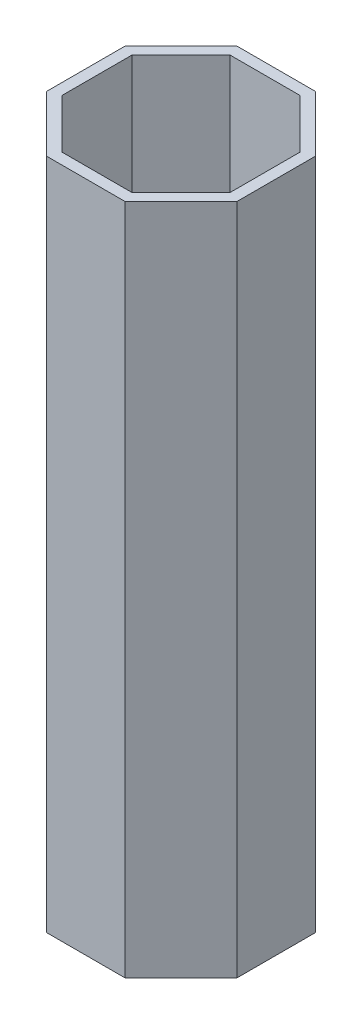
SolidWorks part; units mm, degrees
ref_plane "Alzado" through (0, 0, 0) normal (0, 0, 1) x (1, 0, 0)
ref_plane "Planta" through (0, 0, 0) normal (0, 1, 0) x (1, 0, 0)
ref_plane "Vista lateral" through (0, 0, 0) normal (1, 0, 0) x (0, 0, -1)
sketch "Croquis1" plane through (0, 0, 0) normal (0, 1, 0) x (1, 0, 0)
  line L0 (0, 0) -> (0, 30.3027) construction
  line L1 (17, -7.0416) -> (17, 7.0416)
  line L2 (17, 7.0416) -> (7.0416, 17)
  line L3 (7.0416, 17) -> (-7.0416, 17)
  line L4 (-7.0416, 17) -> (-17, 7.0416)
  line L5 (-17, 7.0416) -> (-17, -7.0416)
  line L6 (-17, -7.0416) -> (-7.0416, -17)
  line L7 (-7.0416, -17) -> (7.0416, -17)
  line L8 (7.0416, -17) -> (17, -7.0416)
  circle A0 centre (0, 0) radius 17 construction
  circle A1 centre (0, 11) radius 1.55
  circle A2 centre (0, 0) radius 4
  circle A3 centre (7.7782, 7.7782) radius 1.55
  circle A4 centre (11, 0) radius 1.55
  circle A5 centre (7.7782, -7.7782) radius 1.55
  circle A6 centre (0, -11) radius 1.55
  circle A7 centre (-7.7782, -7.7782) radius 1.55
  circle A8 centre (-11, 0) radius 1.55
  circle A9 centre (-7.7782, 7.7782) radius 1.55
  point P32 (0, 0)
  dimension "D1" = 34
  dimension "D2" = 3.1
  dimension "D3" = 11
  dimension "D4" = 8
  dimension "D5" = 8
extrude "Saliente-Extruir1" add sketch "Croquis1" along normal blind 120
sketch "Croquis2" plane through (0, 120, 0) normal (0, 1, 0) x (1, 0, 0)
  line L0 (7.0416, 17) -> (-7.0416, 17) construction
  line L1 (6.2132, 15) -> (-6.2132, 15)
  line L2 (-6.2132, 15) -> (-15, 6.2132)
  line L3 (-15, 6.2132) -> (-15, -6.2132)
  line L4 (-15, -6.2132) -> (-6.2132, -15)
  line L5 (-6.2132, -15) -> (6.2132, -15)
  line L6 (6.2132, -15) -> (15, -6.2132)
  line L7 (15, -6.2132) -> (15, 6.2132)
  line L8 (15, 6.2132) -> (6.2132, 15)
  line L9 (-17, 7.0416) -> (-17, -7.0416) construction
  circle A0 centre (0, 0) radius 15 construction
  dimension "D1" = 2
extrude "Cortar-Extruir1" cut sketch "Croquis2" against normal offset from surface (117 mm away) 3 up to face at (0, 0, 0)
